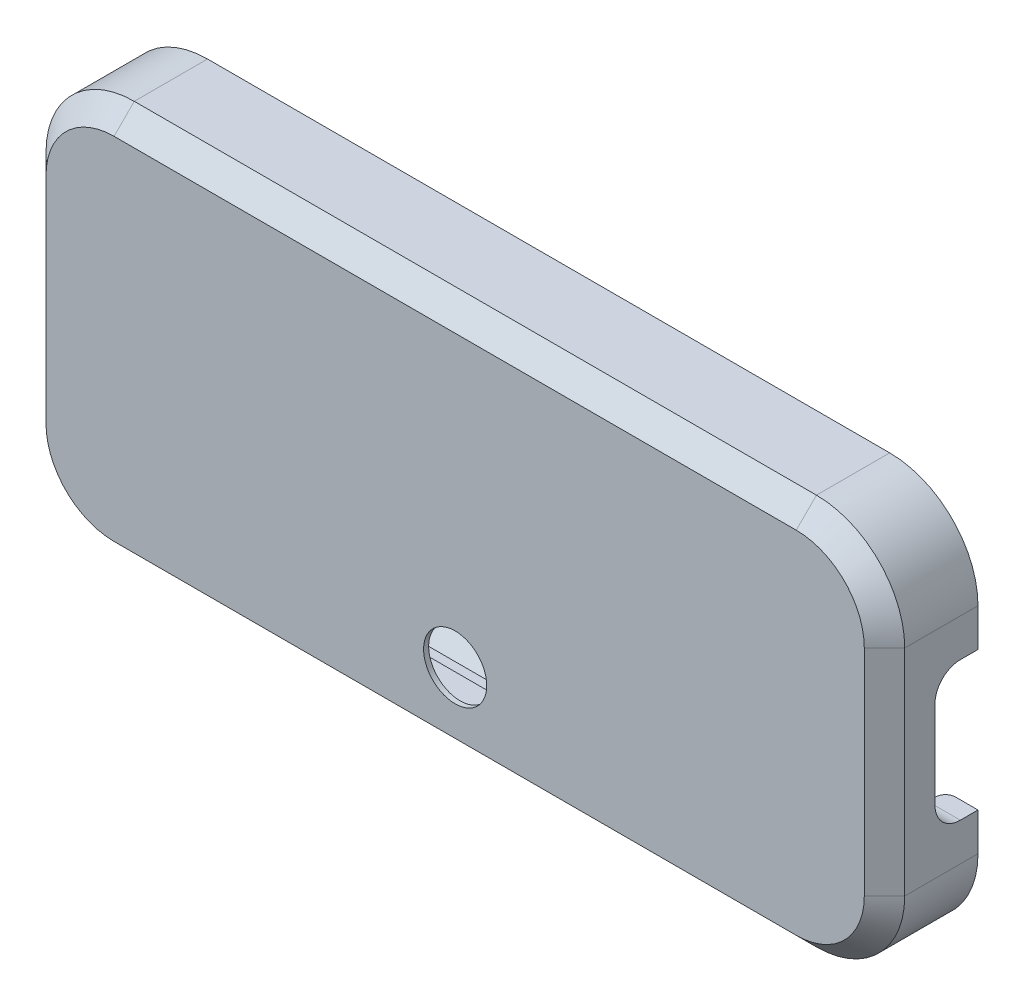
SolidWorks part; units mm, degrees
ref_plane "Ebene vorne" through (0, 0, 0) normal (0, 0, 1) x (1, 0, 0)
ref_plane "Ebene oben" through (0, 0, 0) normal (0, 1, 0) x (1, 0, 0)
ref_plane "Ebene rechts" through (0, 0, 0) normal (1, 0, 0) x (0, 0, -1)
sketch "Skizze1" plane through (0, 0, 2.3001) normal (0, 0, 1) x (1, 0, 0)
  line L0 (-27.9511, -4.5825) -> (-26.1511, -4.5825)
  line L1 (-26.1511, -4.5825) -> (-26.1511, 2.6565)
  line L2 (-26.1511, 2.6565) -> (-22.49, 2.6565)
  line L3 (-22.49, 2.6565) -> (-22.49, -4.5825)
  line L4 (-22.49, -4.5825) -> (-20.69, -4.5825)
  line L5 (-20.69, -4.5825) -> (-20.69, 2.6565)
  line L6 (-20.69, 2.6565) -> (-17.41, 2.6565)
  line L7 (-17.41, 2.6565) -> (-17.41, -4.5825)
  line L8 (-17.41, -4.5825) -> (-15.61, -4.5825)
  line L10 (-16.2652, 4.4565) -> (-27.9511, 4.4565)
  line L11 (-27.9511, 4.4565) -> (-27.9511, -4.5825)
  line L24 (-11.695, 4.4565) -> (-5.069, 4.4565)
  line L25 (-5.069, 4.4565) -> (-5.069, -4.5825)
  line L26 (-5.069, -4.5825) -> (-9.095, -4.5825)
  line L27 (-9.095, -4.5825) -> (-11.695, -4.1241)
  line L28 (-11.695, -4.1241) -> (-11.695, 0.2038)
  line L29 (-11.695, 0.2038) -> (-9.095, 0.9005)
  line L31 (-7.355, -0.8995) -> (-9.895, -0.8995)
  line L32 (-9.895, -0.8995) -> (-9.895, -2.7825)
  line L33 (-9.895, -2.7825) -> (-6.869, -2.7825)
  line L34 (-6.869, -2.7825) -> (-6.869, 2.6565)
  line L35 (-6.869, 2.6565) -> (-11.695, 2.6565)
  line L36 (-11.695, 2.6565) -> (-11.695, 4.4565)
  line L50 (1.259, 8.3935) -> (1.259, 4.4565)
  line L51 (1.259, 4.4565) -> (-1.154, 4.4565)
  line L52 (-1.154, 4.4565) -> (-1.154, 2.6565)
  line L53 (-1.154, 2.6565) -> (1.259, 2.6565)
  line L54 (1.259, 2.6565) -> (1.259, -4.5825)
  line L55 (1.259, -4.5825) -> (5.472, -4.5825)
  line L56 (5.472, -4.5825) -> (5.472, -2.7825)
  line L57 (5.472, -2.7825) -> (3.059, -2.7825)
  line L58 (3.059, -2.7825) -> (3.059, 2.6565)
  line L59 (3.059, 2.6565) -> (5.472, 2.6565)
  line L60 (5.472, 2.6565) -> (5.472, 4.4565)
  line L61 (5.472, 4.4565) -> (3.059, 4.4565)
  line L62 (3.059, 4.4565) -> (3.059, 8.3935)
  line L63 (3.059, 8.3935) -> (1.259, 8.3935)
  line L64 (-16.01, 0.6435) -> (-16.01, 1.6435) construction
  line L65 (-27.5511, 4.0565) -> (-27.5511, 3.0565) construction
  line L66 (-26.5511, -1.7695) -> (-26.5511, -0.7695) construction
  line L67 (-22.09, 1.6435) -> (-22.09, 0.6435) construction
  line L68 (-21.09, 0.6435) -> (-21.09, 1.6435) construction
  line L69 (-20.312, 3.0565) -> (-19.312, 3.0565) construction
  line L70 (-15.61, 2.6565) -> (-16.2652, 4.4565)
  line L71 (-24.138, 4.0565) -> (-25.138, 4.0565) construction
  line L72 (-27.5511, -4.1825) -> (-26.5511, -4.1825) construction
  line L73 (-17.01, 1.6435) -> (-17.01, 0.6435) construction
  line L74 (19.928, 8.2665) -> (19.928, -4.5825)
  line L75 (19.928, -4.5825) -> (21.728, -4.5825)
  line L76 (21.728, -4.5825) -> (21.728, 2.6565)
  line L77 (21.728, 2.6565) -> (25.8971, 2.6565)
  line L78 (25.8971, 2.6565) -> (25.8971, -4.5825)
  line L79 (25.8971, -4.5825) -> (27.6971, -4.5825)
  line L80 (27.6971, -4.5825) -> (27.6971, 2.6565)
  line L83 (27.0419, 4.4565) -> (21.728, 4.4565)
  line L84 (21.728, 4.4565) -> (21.728, 8.2665)
  line L85 (21.728, 8.2665) -> (19.928, 8.2665)
  line L86 (16.013, 2.6565) -> (12.057, 2.6565)
  line L87 (12.057, 2.6565) -> (11.187, 1.7865)
  line L88 (11.187, 1.7865) -> (11.187, -1.9125)
  line L89 (11.187, -1.9125) -> (12.057, -2.7825)
  line L90 (12.057, -2.7825) -> (16.013, -2.7825)
  line L91 (16.013, -2.7825) -> (16.013, -4.5825)
  line L92 (16.013, -4.5825) -> (11.155, -4.5825)
  line L93 (11.155, -4.5825) -> (9.387, -3.099)
  line L94 (9.387, -3.099) -> (9.387, 2.973)
  line L95 (9.387, 2.973) -> (11.155, 4.4565)
  line L96 (11.155, 4.4565) -> (16.013, 4.4565)
  line L97 (16.013, 4.4565) -> (16.013, 2.6565)
  line L98 (-0.754, 4.0565) -> (-0.754, 3.0565) construction
  line L99 (0.246, 4.0565) -> (-0.754, 4.0565) construction
  line L100 (1.659, 5.1995) -> (1.659, 4.1995) construction
  line L101 (2.659, 7.9935) -> (1.659, 7.9935) construction
  line L102 (2.659, 6.9935) -> (2.659, 7.9935) construction
  line L103 (5.072, 3.0565) -> (5.072, 4.0565) construction
  line L104 (4.072, 3.0565) -> (5.072, 3.0565) construction
  line L105 (2.659, 1.4055) -> (2.659, 2.4055) construction
  line L106 (5.072, -4.1825) -> (5.072, -3.1825) construction
  line L107 (5.072, -3.1825) -> (4.072, -3.1825) construction
  line L108 (1.659, -4.1825) -> (2.659, -4.1825) construction
  line L109 (9.787, 0.3735) -> (9.787, -0.6265) construction
  line L110 (10.787, -0.6265) -> (10.787, 0.3735) construction
  line L111 (-11.295, 4.0565) -> (-11.295, 3.0565) construction
  line L112 (-10.295, 4.0565) -> (-11.295, 4.0565) construction
  line L113 (14.613, 3.0565) -> (15.613, 3.0565) construction
  line L114 (15.613, 3.0565) -> (15.613, 4.0565) construction
  line L115 (13.2, 4.0565) -> (12.2, 4.0565) construction
  line L116 (12.2, -4.1825) -> (13.2, -4.1825) construction
  line L117 (20.328, -0.2615) -> (20.328, -1.2615) construction
  line L118 (21.328, -1.2615) -> (21.328, -0.2615) construction
  line L119 (22.741, 3.0565) -> (23.741, 3.0565) construction
  line L120 (26.2971, 1.7705) -> (26.2971, 0.7705) construction
  line L121 (27.2971, 0.7705) -> (27.2971, 1.7705) construction
  line L122 (23.741, 4.0565) -> (22.741, 4.0565) construction
  line L123 (21.328, 7.8665) -> (20.328, 7.8665) construction
  line L124 (21.328, 6.8665) -> (21.328, 7.8665) construction
  line L125 (27.6971, 2.6565) -> (27.0419, 4.4565)
  line L126 (20.328, -4.1825) -> (21.328, -4.1825) construction
  line L127 (-15.61, -4.5825) -> (-15.61, 2.6565)
  line L129 (-11.295, 3.0565) -> (-10.295, 3.0565) construction
  line L130 (-11.295, -0.1345) -> (-11.295, -1.1345) construction
  line L131 (-8.882, -4.1825) -> (-7.882, -4.1825) construction
  line L132 (-5.469, 3.0565) -> (-5.469, 4.0565) construction
  line L134 (-6.469, 1.6435) -> (-6.469, 0.6435) construction
  line L135 (-7.882, -3.1825) -> (-8.882, -3.1825) construction
  line L136 (-10.295, -1.1345) -> (-10.295, -0.1345) construction
  line L137 (-9.095, 0.9005) -> (-7.355, 0.9005)
  line L138 (-7.355, 0.9005) -> (-7.355, -0.8995)
  line L140 (-7.755, 0.5005) -> (-8.755, 0.5005) construction
  line L141 (-4.469, 4.8565) -> (-12.095, 4.8565)
  line L142 (-4.469, 4.8565) -> (-4.469, -5.1825)
  line L143 (-4.469, -5.1825) -> (-12.095, -5.1825)
  line L144 (-12.095, 4.8565) -> (-12.095, -5.1825)
  line L145 (-7.755, -0.4995) -> (-7.755, 0.5005) construction
  line L146 (-8.755, -0.4995) -> (-7.755, -0.4995) construction
  line L147 (-15.9151, 4.9565) -> (-28.4511, 4.9565)
  line L148 (-28.4511, 4.9565) -> (-28.4511, -5.0825)
  line L149 (-28.4511, -5.0825) -> (-25.6511, -5.0825)
  line L150 (-25.6511, -5.0825) -> (-25.6511, 2.1565)
  line L151 (-25.6511, 2.1565) -> (-22.99, 2.1565)
  line L152 (-22.99, 2.1565) -> (-22.99, -5.0825)
  line L153 (-22.99, -5.0825) -> (-20.19, -5.0825)
  line L154 (-20.19, -5.0825) -> (-20.19, 2.1565)
  line L155 (-20.19, 2.1565) -> (-17.91, 2.1565)
  line L156 (-17.91, 2.1565) -> (-17.91, -5.0825)
  line L157 (-17.91, -5.0825) -> (-15.11, -5.0825)
  line L158 (-15.11, -5.0825) -> (-15.11, 2.7447)
  line L159 (-15.11, 2.7447) -> (-15.9151, 4.9565)
  line L160 (5.972, 4.9565) -> (3.559, 4.9565)
  line L161 (3.559, 4.9565) -> (3.559, 8.8935)
  line L162 (3.559, 8.8935) -> (0.759, 8.8935)
  line L163 (0.759, 8.8935) -> (0.759, 4.9565)
  line L164 (0.759, 4.9565) -> (-1.654, 4.9565)
  line L165 (-1.654, 4.9565) -> (-1.654, 2.1565)
  line L166 (-1.654, 2.1565) -> (0.759, 2.1565)
  line L167 (0.759, 2.1565) -> (0.759, -5.0825)
  line L168 (0.759, -5.0825) -> (5.972, -5.0825)
  line L169 (5.972, -5.0825) -> (5.972, -2.2825)
  line L170 (5.972, -2.2825) -> (3.559, -2.2825)
  line L171 (3.559, -2.2825) -> (3.559, 2.1565)
  line L172 (3.559, 2.1565) -> (5.972, 2.1565)
  line L173 (5.972, 2.1565) -> (5.972, 4.9565)
  line L174 (10.973, 4.9565) -> (16.513, 4.9565)
  line L175 (16.513, 4.9565) -> (16.513, 2.1565)
  line L176 (16.513, 2.1565) -> (12.2641, 2.1565)
  line L177 (12.2641, 2.1565) -> (11.687, 1.5794)
  line L178 (11.687, 1.5794) -> (11.687, -1.7054)
  line L179 (11.687, -1.7054) -> (12.2641, -2.2825)
  line L180 (12.2641, -2.2825) -> (16.513, -2.2825)
  line L181 (16.513, -2.2825) -> (16.513, -5.0825)
  line L182 (16.513, -5.0825) -> (10.973, -5.0825)
  line L183 (10.973, -5.0825) -> (8.887, -3.3322)
  line L184 (8.887, -3.3322) -> (8.887, 3.2062)
  line L185 (8.887, 3.2062) -> (10.973, 4.9565)
  line L186 (27.322, 4.8565) -> (22.128, 4.8565)
  line L187 (22.128, 4.8565) -> (22.128, 8.6665)
  line L188 (22.128, 8.6665) -> (19.528, 8.6665)
  line L189 (19.528, 8.6665) -> (19.528, -4.9825)
  line L190 (19.528, -4.9825) -> (22.128, -4.9825)
  line L191 (22.128, -4.9825) -> (22.128, 2.2565)
  line L192 (22.128, 2.2565) -> (25.4971, 2.2565)
  line L193 (25.4971, 2.2565) -> (25.4971, -4.9825)
  line L194 (25.4971, -4.9825) -> (28.0971, -4.9825)
  line L195 (28.0971, -4.9825) -> (28.0971, 2.727)
  line L196 (28.0971, 2.727) -> (27.322, 4.8565)
  dimension "D1" = 0.4
  dimension "D2" = 0.4
  dimension "D3" = 0.4
  dimension "D4" = 0.4
  dimension "D5" = 0.4
  dimension "D7" = 0.4
  dimension "D8" = 0.4
  dimension "D9" = 0.4
  dimension "D10" = 0.4
  dimension "D11" = 0.4
  dimension "D12" = 0.4
  dimension "D13" = 0.4
  dimension "D14" = 0.4
  dimension "D15" = 0.4
  dimension "D16" = 0.4
  dimension "D17" = 0.4
  dimension "D18" = 0.4
  dimension "D19" = 0.4
  dimension "D20" = 0.4
  dimension "D21" = 0.4
  dimension "D22" = 0.4
  dimension "D23" = 0.4
  dimension "D24" = 0.4
  dimension "D25" = 0.4
  dimension "D26" = 0.4
  dimension "D27" = 130
  dimension "D28" = 135
  dimension "D29" = 0.4
  dimension "D30" = 0.4
  dimension "D31" = 0.4
  dimension "D32" = 0.4
  dimension "D33" = 0.4
  dimension "D34" = 0.4
  dimension "D35" = 0.4
  dimension "D36" = 0.4
  dimension "D37" = 0.4
  dimension "D38" = 0.4
  dimension "D39" = 20
  dimension "D40" = 0.4
  dimension "D6" = 0.4
  dimension "D41" = 200
  dimension "D42" = 0.4
  dimension "D43" = 0.4
  dimension "D44" = 0.4
  dimension "D45" = 0.4
  dimension "D46" = 0.4
  dimension "D47" = 0.4
  dimension "D48" = 0.4
  dimension "D49" = 0.4
  dimension "D50" = 0.4
  dimension "D51" = 105
  dimension "D52" = 0.4
  dimension "D53" = 0.4
  dimension "D54" = 0.4
  dimension "D55" = 2.6
  dimension "D56" = 0.4
  dimension "D58" = 0.6
  dimension "D59" = 0.4
  dimension "D57" = 10
  dimension "D64" = 2.6
  dimension "D65" = 0.6
  dimension "D60" = 0.5
  dimension "D61" = 0.5
  dimension "D62" = 0.5
  dimension "D63" = 0.4
extrude "Aufsatz-Linear austragen1" add sketch "Skizze1" along normal blind 1.5
sketch "Skizze2" plane through (0, 0, 3.8001) normal (0, 0, 1) x (1, 0, 0)
  line L0 (30.9874, 8.5) -> (30.9874, -8.5) construction
  line L1 (27.0001, -12.4873) -> (-27.0001, -12.4873) construction
  line L2 (-30.9874, -8.5) -> (-30.9874, 8.5) construction
  line L3 (-27.0001, 12.4873) -> (27.0001, 12.4873) construction
  line L4 (30.9874, 8.5) -> (30.9874, -8.5) construction
  line L5 (27.0001, -12.4873) -> (-27.0001, -12.4873) construction
  line L6 (-30.9874, -8.5) -> (-30.9874, 8.5) construction
  line L7 (-27.0001, 12.4873) -> (27.0001, 12.4873) construction
  line L8 (-27.0001, 15.4873) -> (27.0001, 15.4873)
  line L9 (33.9874, 8.5) -> (33.9874, -8.5)
  line L10 (27.0001, -15.4873) -> (-27.0001, -15.4873)
  line L11 (-33.9874, -8.5) -> (-33.9874, 8.5)
  arc A0 (30.9874, 8.5) -> (27.0001, 12.4873) centre (27.0001, 8.5) ccw construction
  arc A1 (27.0001, -12.4873) -> (30.9874, -8.5) centre (27.0001, -8.5) ccw construction
  arc A2 (-30.9874, -8.5) -> (-27.0001, -12.4873) centre (-27.0001, -8.5) ccw construction
  arc A3 (-27.0001, 12.4873) -> (-30.9874, 8.5) centre (-27.0001, 8.5) ccw construction
  arc A4 (30.9874, 8.5) -> (27.0001, 12.4873) centre (27.0001, 8.5) ccw construction
  arc A5 (27.0001, -12.4873) -> (30.9874, -8.5) centre (27.0001, -8.5) ccw construction
  arc A6 (-30.9874, -8.5) -> (-27.0001, -12.4873) centre (-27.0001, -8.5) ccw construction
  arc A7 (-27.0001, 12.4873) -> (-30.9874, 8.5) centre (-27.0001, 8.5) ccw construction
  circle A8 centre (0, -9.017) radius 2.5
  arc A9 (0.7218, -9.017) -> (-0.7218, -9.017) centre (0, -9.017) ccw construction
  arc A10 (0.7218, -9.017) -> (-0.7218, -9.017) centre (0, -9.017) ccw construction
  arc A11 (33.9874, 8.5) -> (27.0001, 15.4873) centre (27.0001, 8.5) ccw
  arc A12 (27.0001, -15.4873) -> (33.9874, -8.5) centre (27.0001, -8.5) ccw
  arc A13 (-33.9874, -8.5) -> (-27.0001, -15.4873) centre (-27.0001, -8.5) ccw
  arc A14 (-27.0001, 15.4873) -> (-33.9874, 8.5) centre (-27.0001, 8.5) ccw
  dimension "D1" = 5
  dimension "D2" = 3
extrude "Aufsatz-Linear austragen2" add sketch "Skizze2" along normal blind 0.4
sketch "Skizze3" plane through (0, 0, 3.8001) normal (0, 0, -1) x (-1, 0, 0)
  line L12 (-27.225, 11.925) -> (27.225, 11.925)
  line L13 (-27.225, -12.725) -> (27.225, -12.725)
  line L14 (-31.225, -8.725) -> (-31.225, 8.725)
  line L15 (-27.225, 12.725) -> (27.225, 12.725)
  line L16 (31.225, -8.725) -> (31.225, 8.725)
  line L17 (-31.225, -12.725) -> (31.225, 12.725) construction
  line L18 (-31.225, 12.725) -> (31.225, -12.725) construction
  line L19 (30.425, -8.725) -> (30.425, 8.725)
  line L20 (-27.225, -11.925) -> (27.225, -11.925)
  line L21 (-30.425, -8.725) -> (-30.425, 8.725)
  arc A12 (27.225, 12.725) -> (31.225, 8.725) centre (27.225, 8.725) cw
  arc A13 (27.225, -12.725) -> (31.225, -8.725) centre (27.225, -8.725) ccw
  arc A14 (-31.225, -8.725) -> (-27.225, -12.725) centre (-27.225, -8.725) ccw
  arc A15 (-31.225, 8.725) -> (-27.225, 12.725) centre (-27.225, 8.725) cw
  arc A16 (27.225, 11.925) -> (30.425, 8.725) centre (27.225, 8.725) cw
  arc A17 (27.225, -11.925) -> (30.425, -8.725) centre (27.225, -8.725) ccw
  arc A18 (-30.425, -8.725) -> (-27.225, -11.925) centre (-27.225, -8.725) ccw
  arc A19 (-30.425, 8.725) -> (-27.225, 11.925) centre (-27.225, 8.725) cw
  point P0 (0, 0)
  dimension "D3" = 4
  dimension "D1" = 62.45
  dimension "D2" = 25.45
  dimension "D4" = 0.8
extrude "Aufsatz-Linear austragen3" add sketch "Skizze3" along normal blind 2.2
sketch "Skizze10" plane through (0, 0, 3.8001) normal (0, 0, -1) x (-1, 0, 0)
  line L0 (27.225, 12.725) -> (-27.225, 12.725) construction
  line L1 (27.225, 12.725) -> (-27.225, 12.725)
  line L4 (27.0001, 15.4873) -> (-27.0001, 15.4873)
  line L5 (-33.9874, 8.5) -> (-33.9874, -8.5)
  line L6 (-27.0001, -15.4873) -> (27.0001, -15.4873)
  line L7 (33.9874, -8.5) -> (33.9874, 8.5)
  line L8 (27.0001, 15.4873) -> (-27.0001, 15.4873)
  line L9 (-33.9874, 8.5) -> (-33.9874, -8.5)
  line L10 (-27.0001, -15.4873) -> (27.0001, -15.4873)
  line L11 (33.9874, -8.5) -> (33.9874, 8.5)
  line L14 (31.225, -8.725) -> (31.225, 8.725)
  line L15 (31.225, -8.725) -> (31.225, 8.725)
  line L16 (-27.225, -12.725) -> (27.225, -12.725)
  line L17 (-27.225, -12.725) -> (27.225, -12.725)
  line L22 (-31.225, 8.725) -> (-31.225, -8.725)
  line L23 (-31.225, 8.725) -> (-31.225, -8.725)
  line L24 (27.225, 12.725) -> (-27.225, 12.725)
  line L25 (27.225, 12.725) -> (-27.225, 12.725)
  arc A1 (27.225, -12.725) -> (31.225, -8.725) centre (27.225, -8.725) ccw
  arc A4 (33.9874, 8.5) -> (27.0001, 15.4873) centre (27.0001, 8.5) ccw
  arc A5 (-27.0001, 15.4873) -> (-33.9874, 8.5) centre (-27.0001, 8.5) ccw
  arc A6 (-33.9874, -8.5) -> (-27.0001, -15.4873) centre (-27.0001, -8.5) ccw
  arc A7 (27.0001, -15.4873) -> (33.9874, -8.5) centre (27.0001, -8.5) ccw
  arc A8 (33.9874, 8.5) -> (27.0001, 15.4873) centre (27.0001, 8.5) ccw
  arc A9 (-27.0001, 15.4873) -> (-33.9874, 8.5) centre (-27.0001, 8.5) ccw
  arc A10 (-33.9874, -8.5) -> (-27.0001, -15.4873) centre (-27.0001, -8.5) ccw
  arc A11 (27.0001, -15.4873) -> (33.9874, -8.5) centre (27.0001, -8.5) ccw
  arc A15 (27.225, -12.725) -> (31.225, -8.725) centre (27.225, -8.725) ccw
  arc A20 (-31.225, -8.725) -> (-27.225, -12.725) centre (-27.225, -8.725) ccw
  arc A21 (-31.225, -8.725) -> (-27.225, -12.725) centre (-27.225, -8.725) ccw
  arc A22 (-27.225, 12.725) -> (-31.225, 8.725) centre (-27.225, 8.725) ccw
  arc A23 (-27.225, 12.725) -> (-31.225, 8.725) centre (-27.225, 8.725) ccw
  arc A24 (31.225, 8.725) -> (27.225, 12.725) centre (27.225, 8.725) ccw
  arc A25 (31.225, 8.725) -> (27.225, 12.725) centre (27.225, 8.725) ccw
  dimension "D1" = 0
  dimension "D2" = 0
extrude "Aufsatz-Linear austragen14" add sketch "Skizze10" along normal blind 7 contours A8 L8 A9 L9 A10 L10 A11 L11 | L15 A25 L25 A23 L23 A21 L17 A15
sketch "Skizze11" plane through (0, 0, 0) normal (1, 0, 0) x (0, 0, -1)
  line L0 (3.1999, 12.725) -> (-1.6001, 12.725) construction
  line L1 (3.1999, 12.725) -> (-0.1001, 12.725)
  line L2 (-0.1001, 12.725) -> (3.1999, 12.725)
  line L3 (3.1999, 12.725) -> (-0.1001, 13.4264)
  line L4 (-0.1001, 13.4264) -> (-0.1001, 12.725)
  line L5 (-0.1001, 13.4264) -> (3.1999, 12.725)
  line L6 (3.1999, 12.725) -> (-1.6001, 12.725)
  dimension "D1" = 12
  dimension "D2" = 1.5
sketch "Skizze12" plane through (0, 0, -3.1999) normal (0, 0, -1) x (-1, 0, 0)
  line L4 (31.225, -8.725) -> (31.225, 8.725)
  line L16 (31.225, -8.725) -> (31.225, 8.725)
  line L20 (-27.225, -12.725) -> (27.225, -12.725)
  line L22 (-27.225, -12.725) -> (27.225, -12.725)
  line L24 (-31.225, 8.725) -> (-31.225, -8.725)
  line L25 (-31.225, 8.725) -> (-31.225, -8.725)
  line L26 (27.225, 12.725) -> (-27.225, 12.725)
  line L27 (27.225, 12.725) -> (-27.225, 12.725)
  arc A4 (27.225, -12.725) -> (31.225, -8.725) centre (27.225, -8.725) ccw
  arc A16 (27.225, -12.725) -> (31.225, -8.725) centre (27.225, -8.725) ccw
  arc A20 (-31.225, -8.725) -> (-27.225, -12.725) centre (-27.225, -8.725) ccw
  arc A22 (-31.225, -8.725) -> (-27.225, -12.725) centre (-27.225, -8.725) ccw
  arc A24 (-27.225, 12.725) -> (-31.225, 8.725) centre (-27.225, 8.725) ccw
  arc A25 (-27.225, 12.725) -> (-31.225, 8.725) centre (-27.225, 8.725) ccw
  arc A26 (31.225, 8.725) -> (27.225, 12.725) centre (27.225, 8.725) ccw
  arc A27 (31.225, 8.725) -> (27.225, 12.725) centre (27.225, 8.725) ccw
  dimension "D1" = 0
sketch "Skizze14" plane through (0, 0, 3.8001) normal (0, 0, -1) x (-1, 0, 0)
  line L4 (27.225, 11.925) -> (-27.225, 11.925)
  line L5 (-30.425, 8.725) -> (-30.425, -8.725)
  line L6 (-27.225, -11.925) -> (27.225, -11.925)
  line L7 (30.425, -8.725) -> (30.425, 8.725)
  line L8 (27.225, 11.925) -> (-27.225, 11.925)
  line L9 (-30.425, 8.725) -> (-30.425, -8.725)
  line L10 (-27.225, -11.925) -> (27.225, -11.925)
  line L11 (30.425, -8.725) -> (30.425, 8.725)
  line L12 (4.469, -5.1825) -> (12.095, -5.1825)
  line L13 (4.469, 4.8565) -> (4.469, -5.1825)
  line L14 (12.095, 4.8565) -> (4.469, 4.8565)
  line L15 (12.095, -5.1825) -> (12.095, 4.8565)
  line L16 (4.469, -5.1825) -> (12.095, -5.1825)
  line L17 (4.469, 4.8565) -> (4.469, -5.1825)
  line L18 (12.095, 4.8565) -> (4.469, 4.8565)
  line L19 (12.095, -5.1825) -> (12.095, 4.8565)
  line L21 (15.9151, 4.9565) -> (15.11, 2.7447)
  line L22 (28.4511, 4.9565) -> (15.9151, 4.9565)
  line L23 (28.4511, -5.0825) -> (28.4511, 4.9565)
  line L24 (25.6511, -5.0825) -> (28.4511, -5.0825)
  line L25 (25.6511, 2.1565) -> (25.6511, -5.0825)
  line L26 (22.99, 2.1565) -> (25.6511, 2.1565)
  line L27 (22.99, -5.0825) -> (22.99, 2.1565)
  line L28 (20.19, -5.0825) -> (22.99, -5.0825)
  line L29 (20.19, 2.1565) -> (20.19, -5.0825)
  line L30 (17.91, 2.1565) -> (20.19, 2.1565)
  line L31 (17.91, -5.0825) -> (17.91, 2.1565)
  line L32 (15.11, -5.0825) -> (17.91, -5.0825)
  line L33 (15.11, 2.7447) -> (15.11, -5.0825)
  line L34 (15.9151, 4.9565) -> (15.11, 2.7447)
  line L35 (28.4511, 4.9565) -> (15.9151, 4.9565)
  line L36 (28.4511, -5.0825) -> (28.4511, 4.9565)
  line L37 (25.6511, -5.0825) -> (28.4511, -5.0825)
  line L38 (25.6511, 2.1565) -> (25.6511, -5.0825)
  line L39 (22.99, 2.1565) -> (25.6511, 2.1565)
  line L40 (22.99, -5.0825) -> (22.99, 2.1565)
  line L41 (20.19, -5.0825) -> (22.99, -5.0825)
  line L42 (20.19, 2.1565) -> (20.19, -5.0825)
  line L43 (17.91, 2.1565) -> (20.19, 2.1565)
  line L44 (17.91, -5.0825) -> (17.91, 2.1565)
  line L45 (15.11, -5.0825) -> (17.91, -5.0825)
  line L46 (15.11, 2.7447) -> (15.11, -5.0825)
  line L53 (-27.322, 4.8565) -> (-28.0971, 2.727)
  line L54 (-8.887, 3.2062) -> (-10.973, 4.9565)
  line L55 (-8.887, -3.3322) -> (-8.887, 3.2062)
  line L56 (-5.972, 4.9565) -> (-5.972, 2.1565)
  line L57 (-3.559, 4.9565) -> (-5.972, 4.9565)
  line L58 (-3.559, 8.8935) -> (-3.559, 4.9565)
  line L59 (-0.759, 8.8935) -> (-3.559, 8.8935)
  line L60 (-0.759, 4.9565) -> (-0.759, 8.8935)
  line L61 (1.654, 4.9565) -> (-0.759, 4.9565)
  line L62 (1.654, 2.1565) -> (1.654, 4.9565)
  line L63 (-0.759, 2.1565) -> (1.654, 2.1565)
  line L64 (-0.759, -5.0825) -> (-0.759, 2.1565)
  line L65 (-5.972, -5.0825) -> (-0.759, -5.0825)
  line L66 (-5.972, -2.2825) -> (-5.972, -5.0825)
  line L67 (-3.559, -2.2825) -> (-5.972, -2.2825)
  line L68 (-3.559, 2.1565) -> (-3.559, -2.2825)
  line L69 (-5.972, 2.1565) -> (-3.559, 2.1565)
  line L70 (-5.972, 4.9565) -> (-5.972, 2.1565)
  line L71 (-3.559, 4.9565) -> (-5.972, 4.9565)
  line L72 (-3.559, 8.8935) -> (-3.559, 4.9565)
  line L73 (-0.759, 8.8935) -> (-3.559, 8.8935)
  line L74 (-0.759, 4.9565) -> (-0.759, 8.8935)
  line L75 (1.654, 4.9565) -> (-0.759, 4.9565)
  line L76 (1.654, 2.1565) -> (1.654, 4.9565)
  line L77 (-0.759, 2.1565) -> (1.654, 2.1565)
  line L78 (-0.759, -5.0825) -> (-0.759, 2.1565)
  line L79 (-5.972, -5.0825) -> (-0.759, -5.0825)
  line L80 (-5.972, -2.2825) -> (-5.972, -5.0825)
  line L81 (-3.559, -2.2825) -> (-5.972, -2.2825)
  line L82 (-3.559, 2.1565) -> (-3.559, -2.2825)
  line L83 (-5.972, 2.1565) -> (-3.559, 2.1565)
  line L84 (-10.973, -5.0825) -> (-8.887, -3.3322)
  line L85 (-16.513, -5.0825) -> (-10.973, -5.0825)
  line L86 (-16.513, -2.2825) -> (-16.513, -5.0825)
  line L87 (-12.2641, -2.2825) -> (-16.513, -2.2825)
  line L88 (-11.687, -1.7054) -> (-12.2641, -2.2825)
  line L89 (-11.687, 1.5794) -> (-11.687, -1.7054)
  line L90 (-12.2641, 2.1565) -> (-11.687, 1.5794)
  line L91 (-16.513, 2.1565) -> (-12.2641, 2.1565)
  line L92 (-16.513, 4.9565) -> (-16.513, 2.1565)
  line L93 (-10.973, 4.9565) -> (-16.513, 4.9565)
  line L94 (-8.887, 3.2062) -> (-10.973, 4.9565)
  line L95 (-8.887, -3.3322) -> (-8.887, 3.2062)
  line L96 (-10.973, -5.0825) -> (-8.887, -3.3322)
  line L97 (-16.513, -5.0825) -> (-10.973, -5.0825)
  line L98 (-16.513, -2.2825) -> (-16.513, -5.0825)
  line L99 (-12.2641, -2.2825) -> (-16.513, -2.2825)
  line L100 (-11.687, -1.7054) -> (-12.2641, -2.2825)
  line L101 (-11.687, 1.5794) -> (-11.687, -1.7054)
  line L102 (-12.2641, 2.1565) -> (-11.687, 1.5794)
  line L103 (-16.513, 2.1565) -> (-12.2641, 2.1565)
  line L104 (-16.513, 4.9565) -> (-16.513, 2.1565)
  line L105 (-10.973, 4.9565) -> (-16.513, 4.9565)
  line L106 (-22.128, 4.8565) -> (-27.322, 4.8565)
  line L107 (-22.128, 8.6665) -> (-22.128, 4.8565)
  line L108 (-19.528, 8.6665) -> (-22.128, 8.6665)
  line L109 (-19.528, -4.9825) -> (-19.528, 8.6665)
  line L110 (-22.128, -4.9825) -> (-19.528, -4.9825)
  line L111 (-22.128, 2.2565) -> (-22.128, -4.9825)
  line L112 (-25.4971, 2.2565) -> (-22.128, 2.2565)
  line L113 (-25.4971, -4.9825) -> (-25.4971, 2.2565)
  line L114 (-28.0971, -4.9825) -> (-25.4971, -4.9825)
  line L115 (-28.0971, 2.727) -> (-28.0971, -4.9825)
  line L116 (-27.322, 4.8565) -> (-28.0971, 2.727)
  line L117 (-22.128, 4.8565) -> (-27.322, 4.8565)
  line L118 (-22.128, 8.6665) -> (-22.128, 4.8565)
  line L119 (-19.528, 8.6665) -> (-22.128, 8.6665)
  line L120 (-19.528, -4.9825) -> (-19.528, 8.6665)
  line L121 (-22.128, -4.9825) -> (-19.528, -4.9825)
  line L122 (-22.128, 2.2565) -> (-22.128, -4.9825)
  line L123 (-25.4971, 2.2565) -> (-22.128, 2.2565)
  line L124 (-25.4971, -4.9825) -> (-25.4971, 2.2565)
  line L125 (-28.0971, -4.9825) -> (-25.4971, -4.9825)
  line L126 (-28.0971, 2.727) -> (-28.0971, -4.9825)
  circle A1 centre (0, -9.017) radius 2.5
  circle A2 centre (0, -9.017) radius 2.5
  arc A4 (30.425, 8.725) -> (27.225, 11.925) centre (27.225, 8.725) ccw
  arc A5 (-27.225, 11.925) -> (-30.425, 8.725) centre (-27.225, 8.725) ccw
  arc A6 (-30.425, -8.725) -> (-27.225, -11.925) centre (-27.225, -8.725) ccw
  arc A7 (27.225, -11.925) -> (30.425, -8.725) centre (27.225, -8.725) ccw
  arc A8 (30.425, 8.725) -> (27.225, 11.925) centre (27.225, 8.725) ccw
  arc A9 (-27.225, 11.925) -> (-30.425, 8.725) centre (-27.225, 8.725) ccw
  arc A10 (-30.425, -8.725) -> (-27.225, -11.925) centre (-27.225, -8.725) ccw
  arc A11 (27.225, -11.925) -> (30.425, -8.725) centre (27.225, -8.725) ccw
  dimension "D1" = 0
  dimension "D2" = 0
  dimension "D3" = 0
  dimension "D4" = 0
  dimension "D5" = 0
  dimension "D6" = 0
  dimension "D7" = 0
extrude "Aufsatz-Linear austragen15" add sketch "Skizze14" along normal blind 0.9
sweep "Schnitt-Austragung1" cut profiles "Skizze11" path "Skizze12"
fillet "Verrundung1" radius 0.8 9 edges at (-30.0534, -11.5534, -3.1999) (0, -12.725, -3.1999) (30.0534, -11.5534, -3.1999) (31.225, 0, -3.1999) (30.0534, 11.5534, -3.1999) (13.6125, 12.725, -3.1999) (-13.6125, 12.725, -3.1999) (-30.0534, 11.5534, -3.1999) (-31.225, 0, -3.1999)
sketch "Skizze13" plane through (33.9874, 0, 0) normal (1, 0, 0) x (0, 0, -1)
  line L0 (3.1999, 8.5) -> (3.1999, -8.5) construction
  line L1 (1.7999, -5.5) -> (3.9999, -5.5)
  line L2 (-0.2001, -3.5) -> (-0.2001, 3.5)
  line L3 (1.7999, 5.5) -> (3.9999, 5.5)
  line L4 (5.9999, -3.5) -> (5.9999, 3.5)
  line L5 (-0.2001, -5.5) -> (5.9999, 5.5) construction
  line L6 (-0.2001, 5.5) -> (5.9999, -5.5) construction
  arc A0 (3.9999, -5.5) -> (5.9999, -3.5) centre (3.9999, -3.5) ccw
  arc A1 (1.7999, -5.5) -> (-0.2001, -3.5) centre (1.7999, -3.5) cw
  arc A2 (1.7999, 5.5) -> (-0.2001, 3.5) centre (1.7999, 3.5) ccw
  arc A3 (5.9999, 3.5) -> (3.9999, 5.5) centre (3.9999, 3.5) ccw
  point P0 (2.8999, 0)
  point P17 (0, 0)
  point P18 (0, 0)
  point P20 (0, 0)
  point P21 (2.7771, 0)
  dimension "D1" = 2
  dimension "D2" = 11
  dimension "D3" = 6.2
  dimension "D4" = 0.3
extrude "Schnitt-Linear austragen1" cut sketch "Skizze13" against normal blind 5 contours L2 A2 L3 A3 L4 A0 L1 A1
sketch "Skizze15" plane through (0, 0, 2.9001) normal (0, 0, -1) x (-1, 0, 0)
  line L0 (-5, -9.017) -> (5, -9.017) construction
  line L1 (-5, -6.109) -> (5, -6.109)
  line L2 (-5, -11.925) -> (5, -11.925)
  line L3 (-27.225, -11.925) -> (27.225, -11.925) construction
  arc A0 (-5, -6.109) -> (-5, -11.925) centre (-5, -9.017) ccw
  arc A1 (5, -11.925) -> (5, -6.109) centre (5, -9.017) ccw
  point P2 (0, -9.017)
  dimension "D1" = 10
extrude "Schnitt-Linear austragen2" cut sketch "Skizze15" against normal blind 0.9
chamfer "Fase1" distance 1.6 angle 45 8 edges at (-31.9408, -13.4408, 4.2001) (0, -15.4873, 4.2001) (-33.9874, 0, 4.2001) (31.9408, -13.4408, 4.2001) (-31.9408, 13.4408, 4.2001) (33.9874, 0, 4.2001) (0, 15.4873, 4.2001) (31.9408, 13.4408, 4.2001)
sketch "Skizze16" plane through (0, 0, 3.8001) normal (0, 0, -1) x (-1, 0, 0)
  line L0 (26.1511, -4.5825) -> (27.9511, -4.5825) construction
  line L1 (27.9511, -4.5825) -> (27.9511, 4.4565) construction
  line L2 (27.9511, 4.4565) -> (16.2652, 4.4565) construction
  line L3 (16.2652, 4.4565) -> (15.61, 2.6565) construction
  line L4 (15.61, 2.6565) -> (15.61, -4.5825) construction
  line L5 (15.61, -4.5825) -> (17.41, -4.5825) construction
  line L6 (17.41, -4.5825) -> (17.41, 2.6565) construction
  line L7 (17.41, 2.6565) -> (20.69, 2.6565) construction
  line L8 (20.69, 2.6565) -> (20.69, -4.5825) construction
  line L9 (20.69, -4.5825) -> (22.49, -4.5825) construction
  line L10 (22.49, -4.5825) -> (22.49, 2.6565) construction
  line L11 (22.49, 2.6565) -> (26.1511, 2.6565) construction
  line L12 (26.1511, 2.6565) -> (26.1511, -4.5825) construction
  line L13 (7.355, 0.9005) -> (7.355, -0.8995) construction
  line L14 (7.355, -0.8995) -> (9.895, -0.8995) construction
  line L15 (9.895, -0.8995) -> (9.895, -2.7825) construction
  line L16 (9.895, -2.7825) -> (6.869, -2.7825) construction
  line L17 (6.869, -2.7825) -> (6.869, 2.6565) construction
  line L18 (6.869, 2.6565) -> (11.695, 2.6565) construction
  line L19 (11.695, 2.6565) -> (11.695, 4.4565) construction
  line L20 (11.695, 4.4565) -> (5.069, 4.4565) construction
  line L21 (5.069, 4.4565) -> (5.069, -4.5825) construction
  line L22 (5.069, -4.5825) -> (9.095, -4.5825) construction
  line L23 (9.095, -4.5825) -> (11.695, -4.1241) construction
  line L24 (11.695, -4.1241) -> (11.695, 0.2038) construction
  line L25 (11.695, 0.2038) -> (9.095, 0.9005) construction
  line L26 (9.095, 0.9005) -> (7.355, 0.9005) construction
  line L27 (-1.259, 4.4565) -> (-1.259, 8.3935) construction
  line L28 (-1.259, 8.3935) -> (-3.059, 8.3935) construction
  line L29 (-3.059, 8.3935) -> (-3.059, 4.4565) construction
  line L30 (-3.059, 4.4565) -> (-5.472, 4.4565) construction
  line L31 (-5.472, 4.4565) -> (-5.472, 2.6565) construction
  line L32 (-5.472, 2.6565) -> (-3.059, 2.6565) construction
  line L33 (-3.059, 2.6565) -> (-3.059, -2.7825) construction
  line L34 (-3.059, -2.7825) -> (-5.472, -2.7825) construction
  line L35 (-5.472, -2.7825) -> (-5.472, -4.5825) construction
  line L36 (-5.472, -4.5825) -> (-1.259, -4.5825) construction
  line L37 (-1.259, -4.5825) -> (-1.259, 2.6565) construction
  line L38 (-1.259, 2.6565) -> (1.154, 2.6565) construction
  line L39 (1.154, 2.6565) -> (1.154, 4.4565) construction
  line L40 (1.154, 4.4565) -> (-1.259, 4.4565) construction
  line L41 (-11.155, 4.4565) -> (-16.013, 4.4565) construction
  line L42 (-16.013, 4.4565) -> (-16.013, 2.6565) construction
  line L43 (-16.013, 2.6565) -> (-12.057, 2.6565) construction
  line L44 (-12.057, 2.6565) -> (-11.187, 1.7865) construction
  line L45 (-11.187, 1.7865) -> (-11.187, -1.9125) construction
  line L46 (-11.187, -1.9125) -> (-12.057, -2.7825) construction
  line L47 (-12.057, -2.7825) -> (-16.013, -2.7825) construction
  line L48 (-16.013, -2.7825) -> (-16.013, -4.5825) construction
  line L49 (-16.013, -4.5825) -> (-11.155, -4.5825) construction
  line L50 (-11.155, -4.5825) -> (-9.387, -3.099) construction
  line L51 (-9.387, -3.099) -> (-9.387, 2.973) construction
  line L52 (-9.387, 2.973) -> (-11.155, 4.4565) construction
  line L53 (-19.928, -4.5825) -> (-19.928, 8.2665) construction
  line L54 (-19.928, 8.2665) -> (-21.728, 8.2665) construction
  line L55 (-21.728, 8.2665) -> (-21.728, 4.4565) construction
  line L56 (-21.728, 4.4565) -> (-27.0419, 4.4565) construction
  line L57 (-27.0419, 4.4565) -> (-27.6971, 2.6565) construction
  line L58 (-27.6971, 2.6565) -> (-27.6971, -4.5825) construction
  line L59 (-27.6971, -4.5825) -> (-25.8971, -4.5825) construction
  line L60 (-25.8971, -4.5825) -> (-25.8971, 2.6565) construction
  line L61 (-25.8971, 2.6565) -> (-21.728, 2.6565) construction
  line L62 (-21.728, 2.6565) -> (-21.728, -4.5825) construction
  line L63 (-21.728, -4.5825) -> (-19.928, -4.5825) construction
  line L64 (26.1511, -4.5825) -> (27.9511, -4.5825)
  line L65 (27.9511, -4.5825) -> (27.9511, 4.4565)
  line L66 (27.9511, 4.4565) -> (16.2652, 4.4565)
  line L67 (16.2652, 4.4565) -> (15.61, 2.6565)
  line L68 (15.61, 2.6565) -> (15.61, -4.5825)
  line L69 (15.61, -4.5825) -> (17.41, -4.5825)
  line L70 (17.41, -4.5825) -> (17.41, 2.6565)
  line L71 (17.41, 2.6565) -> (20.69, 2.6565)
  line L72 (20.69, 2.6565) -> (20.69, -4.5825)
  line L73 (20.69, -4.5825) -> (22.49, -4.5825)
  line L74 (22.49, -4.5825) -> (22.49, 2.6565)
  line L75 (22.49, 2.6565) -> (26.1511, 2.6565)
  line L76 (26.1511, 2.6565) -> (26.1511, -4.5825)
  line L77 (7.355, 0.9005) -> (7.355, -0.8995)
  line L78 (7.355, -0.8995) -> (9.895, -0.8995)
  line L79 (9.895, -0.8995) -> (9.895, -2.7825)
  line L80 (9.895, -2.7825) -> (6.869, -2.7825)
  line L81 (6.869, -2.7825) -> (6.869, 2.6565)
  line L82 (6.869, 2.6565) -> (11.695, 2.6565)
  line L83 (11.695, 2.6565) -> (11.695, 4.4565)
  line L84 (11.695, 4.4565) -> (5.069, 4.4565)
  line L85 (5.069, 4.4565) -> (5.069, -4.5825)
  line L86 (5.069, -4.5825) -> (9.095, -4.5825)
  line L87 (9.095, -4.5825) -> (11.695, -4.1241)
  line L88 (11.695, -4.1241) -> (11.695, 0.2038)
  line L89 (11.695, 0.2038) -> (9.095, 0.9005)
  line L90 (9.095, 0.9005) -> (7.355, 0.9005)
  line L91 (-1.259, 4.4565) -> (-1.259, 8.3935)
  line L92 (-1.259, 8.3935) -> (-3.059, 8.3935)
  line L93 (-3.059, 8.3935) -> (-3.059, 4.4565)
  line L94 (-3.059, 4.4565) -> (-5.472, 4.4565)
  line L95 (-5.472, 4.4565) -> (-5.472, 2.6565)
  line L96 (-5.472, 2.6565) -> (-3.059, 2.6565)
  line L97 (-3.059, 2.6565) -> (-3.059, -2.7825)
  line L98 (-3.059, -2.7825) -> (-5.472, -2.7825)
  line L99 (-5.472, -2.7825) -> (-5.472, -4.5825)
  line L100 (-5.472, -4.5825) -> (-1.259, -4.5825)
  line L101 (-1.259, -4.5825) -> (-1.259, 2.6565)
  line L102 (-1.259, 2.6565) -> (1.154, 2.6565)
  line L103 (1.154, 2.6565) -> (1.154, 4.4565)
  line L104 (1.154, 4.4565) -> (-1.259, 4.4565)
  line L105 (-11.155, 4.4565) -> (-16.013, 4.4565)
  line L106 (-16.013, 4.4565) -> (-16.013, 2.6565)
  line L107 (-16.013, 2.6565) -> (-12.057, 2.6565)
  line L108 (-12.057, 2.6565) -> (-11.187, 1.7865)
  line L109 (-11.187, 1.7865) -> (-11.187, -1.9125)
  line L110 (-11.187, -1.9125) -> (-12.057, -2.7825)
  line L111 (-12.057, -2.7825) -> (-16.013, -2.7825)
  line L112 (-16.013, -2.7825) -> (-16.013, -4.5825)
  line L113 (-16.013, -4.5825) -> (-11.155, -4.5825)
  line L114 (-11.155, -4.5825) -> (-9.387, -3.099)
  line L115 (-9.387, -3.099) -> (-9.387, 2.973)
  line L116 (-9.387, 2.973) -> (-11.155, 4.4565)
  line L117 (-19.928, -4.5825) -> (-19.928, 8.2665)
  line L118 (-19.928, 8.2665) -> (-21.728, 8.2665)
  line L119 (-21.728, 8.2665) -> (-21.728, 4.4565)
  line L120 (-21.728, 4.4565) -> (-27.0419, 4.4565)
  line L121 (-27.0419, 4.4565) -> (-27.6971, 2.6565)
  line L122 (-27.6971, 2.6565) -> (-27.6971, -4.5825)
  line L123 (-27.6971, -4.5825) -> (-25.8971, -4.5825)
  line L124 (-25.8971, -4.5825) -> (-25.8971, 2.6565)
  line L125 (-25.8971, 2.6565) -> (-21.728, 2.6565)
  line L126 (-21.728, 2.6565) -> (-21.728, -4.5825)
  line L127 (-21.728, -4.5825) -> (-19.928, -4.5825)
extrude "Cut_Letters_optional" [suppressed] cut sketch "Skizze16" against normal through all contours L117 L118 L119 L120 L121 L122 L123 L124 L125 L126 L127 | L105 L106 L107 L108 L109 L110 L111 L112 L113 L114 L115 L116 | L91 L92 L93 L94 L95 L96 L97 L98 L99 L100 L101 L102 L103 L104 | L77 L78 L79 L80 L81 L82 L83 L84 L85 L86 L87 L88 L89 L90 | L64 L65 L66 L67 L68 L69 L70 L71 L72 L73 L74 L75 L76
sketch "Skizze17" plane through (0, 0, 4.2001) normal (0, 0, 1) x (1, 0, 0)
  circle A1 centre (0, -9.017) radius 2.5
  circle A2 centre (0, -9.017) radius 2.5
  circle A3 centre (0, -9.017) radius 2.5
  circle A4 centre (0, -9.017) radius 2.5
  circle A5 centre (0, -9.017) radius 2.5
  circle A6 centre (0, -9.017) radius 2.5
  circle A7 centre (0, -9.017) radius 2.5
  circle A8 centre (0, -9.017) radius 2.5
  circle A9 centre (0, -9.017) radius 2.5
  circle A10 centre (0, -9.017) radius 2.5
  dimension "D1" = 0
  dimension "D2" = 0
  dimension "D3" = 0
  dimension "D4" = 0
  dimension "D5" = 0
extrude "Letters_single" [suppressed] add sketch "Skizze17" against normal blind 0.3 separate body
equation "\"D2@Skizze1\"=\"D1@Skizze1\""
equation "\"D3@Skizze1\"=\"D1@Skizze1\""
equation "\"D4@Skizze1\"=\"D1@Skizze1\""
equation "\"D5@Skizze1\"=\"D1@Skizze1\""
equation "\"D7@Skizze1\"=\"D1@Skizze1\""
equation "\"D8@Skizze1\"=\"D1@Skizze1\""
equation "\"D9@Skizze1\"=\"D1@Skizze1\""
equation "\"D11@Skizze1\"=\"D10@Skizze1\""
equation "\"D12@Skizze1\"=\"D10@Skizze1\""
equation "\"D13@Skizze1\"=\"D10@Skizze1\""
equation "\"D14@Skizze1\"=\"D10@Skizze1\""
equation "\"D15@Skizze1\"=\"D10@Skizze1\""
equation "\"D16@Skizze1\"=\"D10@Skizze1\""
equation "\"D17@Skizze1\"=\"D10@Skizze1\""
equation "\"D18@Skizze1\"=\"D10@Skizze1\""
equation "\"D20@Skizze1\"=\"D10@Skizze1\""
equation "\"D22@Skizze1\"=\"D21@Skizze1\""
equation "\"D23@Skizze1\"=\"D21@Skizze1\""
equation "\"D24@Skizze1\"=\"D21@Skizze1\""
equation "\"D25@Skizze1\"=\"D21@Skizze1\""
equation "\"D26@Skizze1\"=\"D21@Skizze1\""
equation "\"D33@Skizze1\"=\"D31@Skizze1\""
equation "\"D34@Skizze1\"=\"D31@Skizze1\""
equation "\"D35@Skizze1\"=\"D31@Skizze1\""
equation "\"D37@Skizze1\"=\"D31@Skizze1\""
equation "\"D38@Skizze1\"=\"D31@Skizze1\""
equation "\"D40@Skizze1\"=\"D31@Skizze1\""
equation "\"D32@Skizze1\"=\"D31@Skizze1\""
equation "\"D6@Skizze1\"=\"D1@Skizze1\""
equation "\"D43@Skizze1\"=\"D42@Skizze1\""
equation "\"D44@Skizze1\"=\"D42@Skizze1\""
equation "\"D45@Skizze1\"=\"D44@Skizze1\""
equation "\"D46@Skizze1\"=\"D42@Skizze1\""
equation "\"D47@Skizze1\"=\"D42@Skizze1\""
equation "\"D48@Skizze1\"=\"D42@Skizze1\""
equation "\"D49@Skizze1\"=\"D42@Skizze1\""
equation "\"D50@Skizze1\"=\"D42@Skizze1\""
equation "\"D54@Skizze1\"=\"D42@Skizze1\""
equation "\"D19@Skizze1\"=\"D10@Skizze1\""
